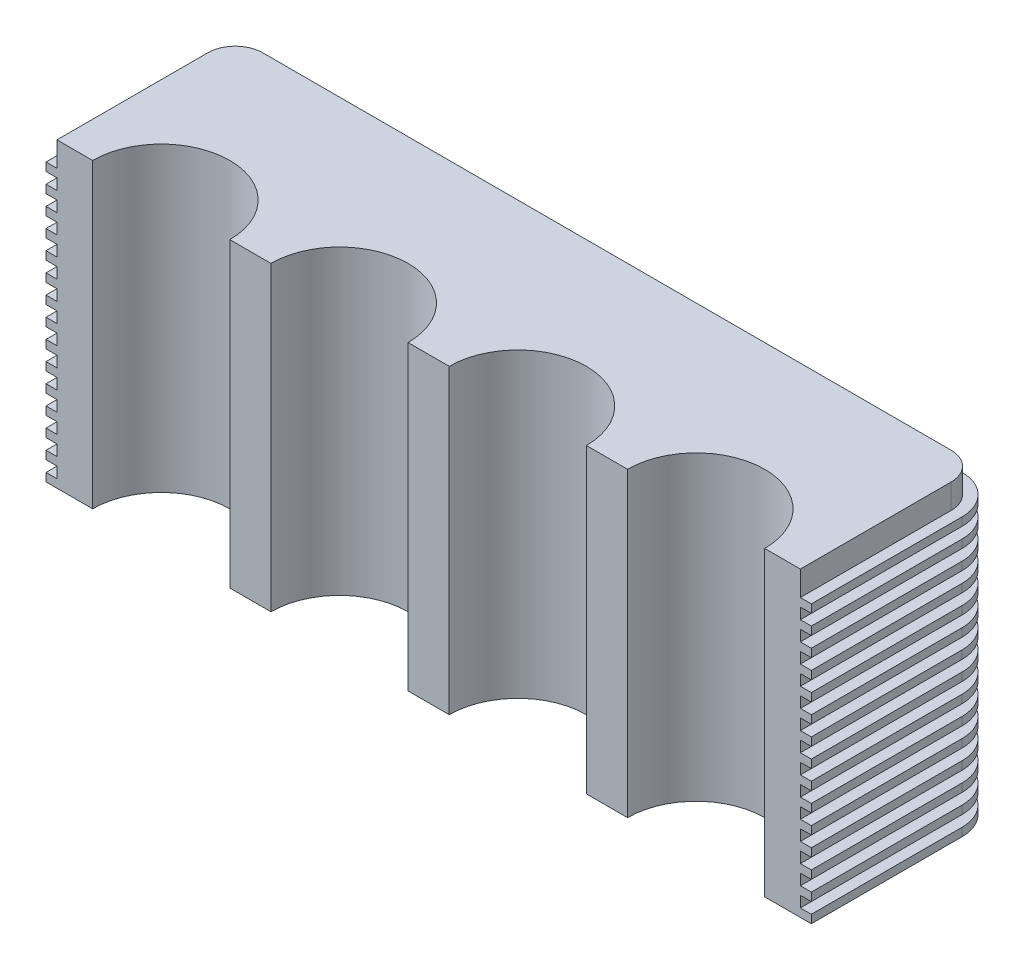
SolidWorks part; units mm, degrees
ref_plane "Front Plane" through (0, 0, 0) normal (0, 0, 1) x (1, 0, 0)
ref_plane "Top Plane" through (0, 0, 0) normal (0, 1, 0) x (1, 0, 0)
ref_plane "Right Plane" through (0, 0, 0) normal (1, 0, 0) x (0, 0, -1)
sketch "Sketch1" plane through (0, 0, 0) normal (0, 1, 0) x (1, 0, 0)
  line L0 (135.5, 0) -> (135.5, 65) construction
  line L1 (0, 0) -> (13, 0)
  line L2 (0, 0) -> (0, 55)
  line L3 (10, 65) -> (261, 65)
  line L4 (271, 0) -> (271, 55)
  line L5 (258, 0) -> (271, 0)
  line L6 (193, 0) -> (208, 0)
  line L7 (63, 0) -> (78, 0)
  line L8 (128, 0) -> (143, 0)
  arc A0 (0, 55) -> (10, 65) centre (10, 55) cw
  arc A1 (271, 55) -> (261, 65) centre (261, 55) ccw
  arc A2 (258, 0) -> (208, 0) centre (233, 0) ccw
  arc A3 (193, 0) -> (143, 0) centre (168, 0) ccw
  arc A4 (78, 0) -> (128, 0) centre (103, 0) cw
  arc A5 (13, 0) -> (63, 0) centre (38, 0) cw
  point P23 (0, 0)
  dimension "D1" = 10
  dimension "D2" = 10
  dimension "D5" = 25
  dimension "D7" = 50
  dimension "D3" = 271
  dimension "D4" = 65
  dimension "D6" = 13
  dimension "D8" = 15
extrude "Boss-Extrude1" add sketch "Sketch1" along normal blind 110
sketch "Sketch2" plane through (0, 0, 0) normal (0, 1, 0) x (1, 0, 0)
  line L0 (275, 0) -> (275, 55)
  line L1 (261, 69) -> (10, 69)
  line L2 (-4, 55) -> (-4, 0)
  line L3 (271, 0) -> (275, 0)
  line L4 (0, 0) -> (-4, 0)
  line L8 (0, 55) -> (0, 0)
  line L9 (0, 0) -> (13, 0)
  line L10 (63, 0) -> (78, 0)
  line L11 (128, 0) -> (143, 0)
  line L12 (193, 0) -> (208, 0)
  line L13 (258, 0) -> (271, 0)
  line L14 (271, 0) -> (271, 55)
  line L15 (261, 65) -> (10, 65)
  line L16 (0, 55) -> (0, 0)
  line L19 (128, 0) -> (143, 0)
  line L22 (271, 0) -> (271, 55)
  line L23 (261, 65) -> (10, 65)
  arc A0 (275, 55) -> (261, 69) centre (261, 55) ccw
  arc A1 (10, 69) -> (-4, 55) centre (10, 55) ccw
  arc A6 (63, 0) -> (13, 0) centre (38, 0) ccw
  arc A7 (128, 0) -> (78, 0) centre (103, 0) ccw
  arc A8 (193, 0) -> (143, 0) centre (168, 0) ccw
  arc A9 (258, 0) -> (208, 0) centre (233, 0) ccw
  arc A10 (271, 55) -> (261, 65) centre (261, 55) ccw
  arc A11 (10, 65) -> (0, 55) centre (10, 55) ccw
  arc A16 (271, 55) -> (261, 65) centre (261, 55) ccw
  arc A17 (10, 65) -> (0, 55) centre (10, 55) ccw
  dimension "D1" = 0
  dimension "D2" = 4
extrude "Boss-Extrude2" add sketch "Sketch2" along normal blind 3 contours L0 A0 L1 A1 L2 L4 L16 A17 L23 A16 L22 L3
pattern_linear "LPattern1" count 15 spacing 7 along (0, 1, 0) of "Boss-Extrude2"
